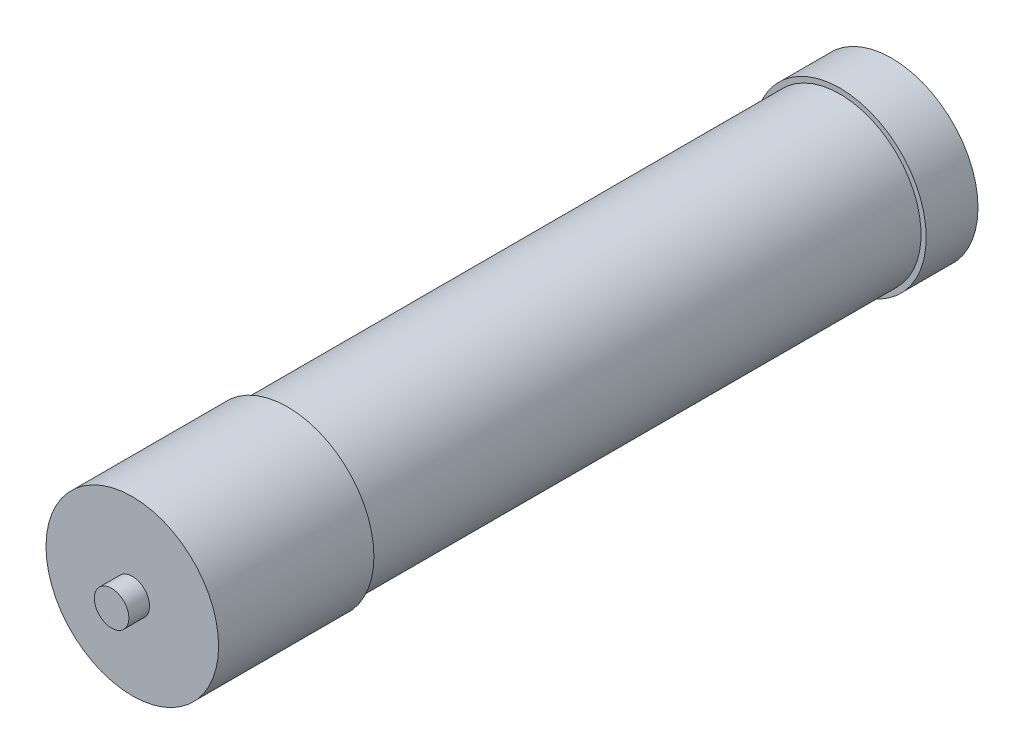
SolidWorks part; units mm, degrees
ref_plane "Front Plane" through (0, 0, 0) normal (0, 0, 1) x (1, 0, 0)
ref_plane "Top Plane" through (0, 0, 0) normal (0, 1, 0) x (1, 0, 0)
ref_plane "Right Plane" through (0, 0, 0) normal (1, 0, 0) x (0, 0, -1)
sketch "Sketch1" plane through (0, 0, 0) normal (0, 0, 1) x (1, 0, 0)
  circle A0 centre (0, 0) radius 23.5
  dimension "D1" = 47
extrude "Boss-Extrude1" add sketch "Sketch1" along normal mid plane 220
sketch "Sketch2" plane through (0, 0, 110) normal (0, 0, 1) x (1, 0, 0)
  circle A0 centre (0, 0) radius 5
  dimension "D1" = 10
extrude "Boss-Extrude2" add sketch "Sketch2" along normal blind 6
sketch "Sketch5" plane through (0, 0, 110) normal (0, 0, 1) x (1, 0, 0)
  circle A0 centre (0, 0) radius 25
  dimension "D1" = 50
extrude "Boss-Extrude5" add sketch "Sketch5" against normal blind 45
sketch "Sketch6" plane through (0, 0, -110) normal (0, 0, -1) x (-1, 0, 0)
  circle A0 centre (0, 0) radius 25
  dimension "D1" = 50
extrude "Boss-Extrude6" add sketch "Sketch6" against normal blind 15
sketch "Sketch8" plane through (0, 0, -110) normal (0, 0, -1) x (-1, 0, 0)
  line L0 (0, 17.5) -> (0, -17.5) construction
  line L1 (-17.5, 0) -> (17.5, 0) construction
  circle A0 centre (0, 0) radius 17.5
  dimension "D1" = 35
hole_wizard "M4x0.7 Tapped Hole1" positions "3DSketch2" profile "Sketch10" tap size "M4x0.7" standard "ANSI Metric"
sketch3d "3DSketch2"
  point P0 (0, 17.5, -110)
  point P3 (-17.5, 0, -110)
  point P6 (0, -17.5, -110)
  point P9 (17.5, 0, -110)
cosmetic thread "Hole Thread1" parameters "D1"=20, "D2"=4
cosmetic thread "Hole Thread2" parameters "D1"=20, "D2"=4
cosmetic thread "Hole Thread3" parameters "D1"=20, "D2"=4
cosmetic thread "Hole Thread4" parameters "D1"=20, "D2"=4
sketch "Sketch10" plane through (0, 17.5, -110) normal (1, 0, 0) x (0, 1, 0)
  line L0 (0, 0) -> (0, 20.9914)
  line L1 (0, 20.9914) -> (1.65, 20)
  line L2 (1.65, 20) -> (1.65, 0)
  line L5 (1.65, 0) -> (0, 0)
  line L10 (0, 20.9914) -> (-1.65, 20) construction
  line L11 (0, -6.35) -> (0, 107.95) construction
  dimension "Tap Drill Dia." = 3.3
  dimension "Tap Drill Depth" = 20
  dimension "Drill Angle" = 118
